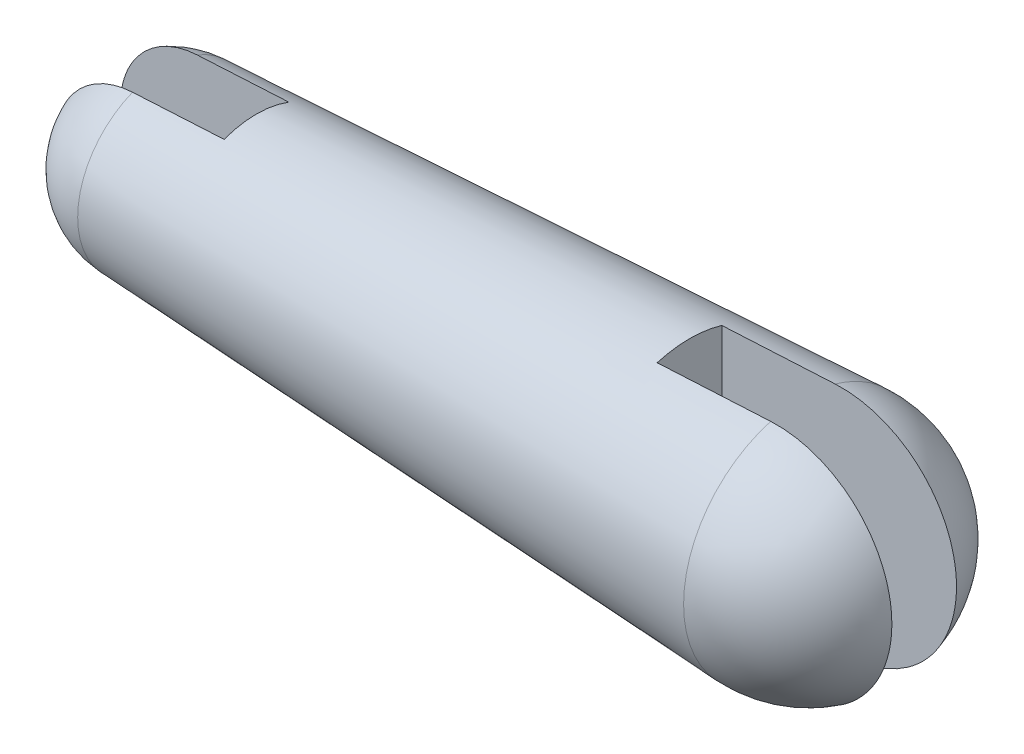
SolidWorks part; units mm, degrees
ref_plane "Front Plane" through (0, 0, 0) normal (0, 0, 1) x (1, 0, 0)
ref_plane "Top Plane" through (0, 0, 0) normal (0, 1, 0) x (1, 0, 0)
ref_plane "Right Plane" through (0, 0, 0) normal (1, 0, 0) x (0, 0, -1)
sketch "Sketch3" plane through (0, 0, 0) normal (0, 1, 0) x (1, 0, 0)
  line L0 (-1000, 0) -> (49000, 0) construction
  line L1 (-125.73, 0) -> (125.73, 0)
  line L2 (-127.4618, 34.2462) -> (123.3568, 46.93)
  line L3 (-160.02, 0) -> (-125.73, 0)
  line L4 (125.73, 0) -> (172.72, 0)
  arc A0 (-127.4618, 34.2462) -> (-160.02, 0) centre (-125.73, 0) ccw
  arc A1 (172.72, 0) -> (123.3568, 46.93) centre (125.73, 0) ccw
  dimension "D3" = 68.58
  dimension "D4" = 93.98
  dimension "D5" = 251.46
revolve "Revolve2" add sketch "Sketch3" angle 360 about L0
sketch "Sketch4" plane through (0, 0, 0) normal (0, 1, 0) x (1, 0, 0)
  line L0 (172.72, -1001.5704) -> (172.72, 48998.4296) construction
  line L1 (78.74, 12.7) -> (172.72, 12.7)
  line L2 (78.74, 12.7) -> (78.74, -12.7)
  line L3 (78.74, -12.7) -> (172.72, -12.7)
  line L4 (172.72, 12.7) -> (172.72, -12.7)
  line L5 (78.74, 12.7) -> (172.72, -12.7) construction
  line L6 (78.74, -12.7) -> (172.72, 12.7) construction
  line L7 (-1000, 0) -> (49000, 0) construction
  line L8 (-160.02, -1000) -> (-160.02, 49000) construction
  line L9 (-160.02, 12.7) -> (-91.44, 12.7)
  line L10 (-160.02, 12.7) -> (-160.02, -12.7)
  line L11 (-160.02, -12.7) -> (-91.44, -12.7)
  line L12 (-91.44, 12.7) -> (-91.44, -12.7)
  line L13 (-160.02, 12.7) -> (-91.44, -12.7) construction
  line L14 (-160.02, -12.7) -> (-91.44, 12.7) construction
  arc A0 (123.3568, -46.93) -> (123.3568, 46.93) centre (125.73, 0) ccw construction
  arc A1 (-127.4618, 34.2462) -> (-127.4618, -34.2462) centre (-125.73, 0) ccw construction
  point P0 (125.73, 0)
  point P11 (-125.73, 0)
  dimension "D1" = 93.98
  dimension "D2" = 25.4
  dimension "D3" = 68.58
  dimension "D4" = 25.4
extrude "Cut-Extrude1" cut sketch "Sketch4" against normal through all and the other way through all
sketch3d "3DSketch1"
  line L0 (-160.02, 0, 0) -> (172.72, 0, 0)
  line L1 (-125.73, 0, -127) -> (-125.73, 0, 127)
  line L2 (125.73, 0, -127) -> (125.73, 0, 127)
  point P7 (-125.73, 0, 0)
  point P8 (125.73, 0, 0)
  point P9 (0, 0, 0)
  point P10 (0, 0, 0)
  point P11 (0, 0, 0)
  dimension "D1" = 125.73
  dimension "D2" = 125.73
  dimension "D3" = 254
